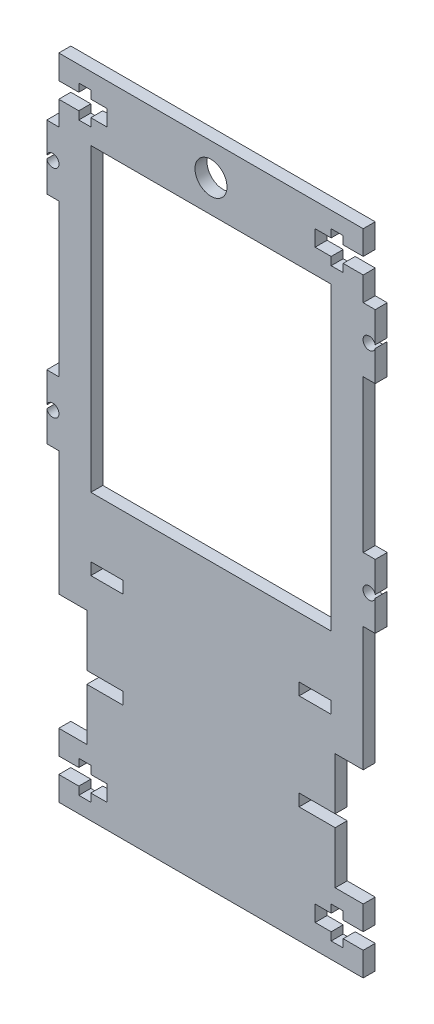
SolidWorks part; units mm, degrees
ref_plane "前视" through (0, 0, 0) normal (0, 0, 1) x (1, 0, 0)
ref_plane "上视" through (0, 0, 0) normal (0, 1, 0) x (1, 0, 0)
ref_plane "右视" through (0, 0, 0) normal (1, 0, 0) x (0, 0, -1)
sketch "草图1" plane through (0, 0, 0) normal (0, 0, 1) x (1, 0, 0)
  line L0 (0, 210.7736) -> (0, 0) construction
  line L2 (-30, 0) -> (-30, 70)
  line L3 (-30, 70) -> (30, 70)
  line L4 (38, 86) -> (-38, 86)
  line L5 (-38, 86) -> (-38, 80)
  line L6 (-38, -76) -> (38, -76)
  line L7 (-57.1558, 78) -> (-15.5606, 78) construction
  line L8 (-38, -31) -> (-31, -31)
  line L9 (-31, -31) -> (-31, -44)
  line L10 (-30, -20) -> (-22, -20)
  line L11 (-30, -20) -> (-30, -23)
  line L12 (-30, -23) -> (-22, -23)
  line L13 (-22, -20) -> (-22, -23)
  line L14 (-31, -60) -> (-38, -60)
  line L15 (-31, -44) -> (-22, -44)
  line L16 (-38, 80) -> (-33, 80)
  line L17 (-33, 80) -> (-33, 82)
  line L18 (-33, 82) -> (-30, 82)
  line L19 (-30, 82) -> (-30, 80)
  line L20 (-30, 80) -> (-26, 80)
  line L21 (-26, 80) -> (-26, 76)
  line L22 (-38, 70) -> (-41, 70)
  line L23 (-41, 70) -> (-41, 62.3905)
  line L24 (-41, 54) -> (-38, 54)
  line L25 (-22, -44) -> (-22, -47)
  line L26 (-22, -47) -> (-31, -47)
  line L27 (-79.0276, -37.5) -> (22.5337, -37.5) construction
  line L28 (-70.3656, -7.5) -> (14.5214, -7.5) construction
  line L29 (-45.3123, -68) -> (-14.2627, -68) construction
  line L30 (-38, -70) -> (-33, -70)
  line L31 (-30, 76) -> (-26, 76)
  line L32 (-30, 74) -> (-30, 76)
  line L33 (-33, 74) -> (-30, 74)
  line L34 (-33, 76) -> (-33, 74)
  line L35 (-38, 76) -> (-33, 76)
  line L36 (-33, -70) -> (-33, -72)
  line L37 (-33, -72) -> (-30, -72)
  line L38 (-30, -72) -> (-30, -70)
  line L39 (-30, -70) -> (-26, -70)
  line L40 (-26, -70) -> (-26, -66)
  line L41 (-30, -66) -> (-26, -66)
  line L42 (-30, -64) -> (-30, -66)
  line L43 (-33, -64) -> (-30, -64)
  line L44 (-33, -66) -> (-33, -64)
  line L45 (-38, -66) -> (-33, -66)
  line L46 (-38, 0) -> (-41, 0)
  line L47 (-41, 0) -> (-41, 7.6095)
  line L48 (-41, 16) -> (-38, 16)
  line L49 (-38, -70) -> (-38, -76)
  line L50 (-38, -60) -> (-38, -66)
  line L51 (-31, -47) -> (-31, -60)
  line L52 (-38, 0) -> (-38, -31)
  line L53 (-38, 54) -> (-38, 16)
  line L54 (-38, 76) -> (-38, 70)
  line L55 (-41, 8.3905) -> (-41, 16)
  line L56 (-41, 61.6095) -> (-41, 54)
  line L57 (45.3123, -68) -> (14.2627, -68) construction
  line L58 (70.3656, -7.5) -> (-14.5214, -7.5) construction
  line L59 (79.0276, -37.5) -> (-22.5337, -37.5) construction
  line L60 (57.1558, 78) -> (15.5606, 78) construction
  line L61 (41, 61.6095) -> (41, 54)
  line L62 (41, 8.3905) -> (41, 16)
  line L63 (38, 76) -> (38, 70)
  line L64 (38, 54) -> (38, 16)
  line L65 (38, 0) -> (38, -31)
  line L66 (31, -47) -> (31, -60)
  line L67 (38, -60) -> (38, -66)
  line L68 (38, -70) -> (38, -76)
  line L69 (41, 16) -> (38, 16)
  line L70 (41, 0) -> (41, 7.6095)
  line L71 (38, 0) -> (41, 0)
  line L72 (38, -66) -> (33, -66)
  line L73 (33, -66) -> (33, -64)
  line L74 (33, -64) -> (30, -64)
  line L75 (30, -64) -> (30, -66)
  line L76 (30, -66) -> (26, -66)
  line L77 (26, -70) -> (26, -66)
  line L78 (30, -70) -> (26, -70)
  line L79 (30, -72) -> (30, -70)
  line L80 (33, -72) -> (30, -72)
  line L81 (33, -70) -> (33, -72)
  line L82 (38, 76) -> (33, 76)
  line L83 (33, 76) -> (33, 74)
  line L84 (33, 74) -> (30, 74)
  line L85 (30, 74) -> (30, 76)
  line L86 (30, 76) -> (26, 76)
  line L87 (38, -70) -> (33, -70)
  line L88 (22, -47) -> (31, -47)
  line L89 (22, -44) -> (22, -47)
  line L90 (41, 54) -> (38, 54)
  line L91 (41, 70) -> (41, 62.3905)
  line L92 (38, 70) -> (41, 70)
  line L93 (26, 80) -> (26, 76)
  line L94 (30, 80) -> (26, 80)
  line L95 (30, 82) -> (30, 80)
  line L96 (33, 82) -> (30, 82)
  line L97 (33, 80) -> (33, 82)
  line L98 (38, 80) -> (33, 80)
  line L99 (31, -44) -> (22, -44)
  line L100 (31, -60) -> (38, -60)
  line L101 (22, -20) -> (22, -23)
  line L102 (30, -23) -> (22, -23)
  line L103 (30, -20) -> (30, -23)
  line L104 (30, -20) -> (22, -20)
  line L105 (31, -31) -> (31, -44)
  line L106 (38, -31) -> (31, -31)
  line L107 (38, 86) -> (38, 80)
  line L108 (30, 0) -> (30, 70)
  line L109 (-30, 0) -> (-30, -5)
  line L110 (-30, -5) -> (30, -5)
  line L111 (30, -5) -> (30, 0)
  line L112 (0, -5) -> (0, -181.9356) construction
  circle A0 centre (0, 78) radius 4
  arc A1 (-41, 7.6095) -> (-41, 8.3905) centre (-39.5, 8) ccw
  arc A2 (-41, 61.6095) -> (-41, 62.3905) centre (-39.5, 62) ccw
  arc A3 (41, 61.6095) -> (41, 62.3905) centre (39.5, 62) cw
  arc A4 (41, 7.6095) -> (41, 8.3905) centre (39.5, 8) cw
  point P2 (26, -68)
  point P42 (-26, 78)
  point P58 (-26, -68)
  point P132 (0, -76)
  point P133 (0, 86)
  point P134 (0, 70)
  point P135 (0, 0)
  point P136 (26, 78)
  dimension "D17" = 1.55
  dimension "D18" = 3
  dimension "D19" = 8
  dimension "D10" = 8
  dimension "D16" = 8
  dimension "D37" = 1.5
  dimension "D38" = 1.5
  dimension "D40" = 1.55
  dimension "D1" = 30
  dimension "D2" = 38
  dimension "D3" = 2
  dimension "D4" = 2
  dimension "D5" = 2
  dimension "D6" = 3
  dimension "D7" = 5
  dimension "D8" = 12
  dimension "D9" = 8
  dimension "D11" = 3
  dimension "D12" = 16
  dimension "D13" = 8
  dimension "D14" = 16
  dimension "D15" = 70
  dimension "D20" = 31
  dimension "D21" = 3
  dimension "D22" = 13
  dimension "D23" = 6.5
  dimension "D24" = 30
  dimension "D25" = 29
  dimension "D26" = 8
  dimension "D27" = 16
  dimension "D28" = 2
  dimension "D29" = 2
  dimension "D30" = 2
  dimension "D31" = 8
  dimension "D32" = 3
  dimension "D33" = 5
  dimension "D34" = 12
  dimension "D35" = 3
  dimension "D36" = 16
  dimension "D39" = 5
extrude "凸台-拉伸1" add sketch "草图1" along normal blind 3
